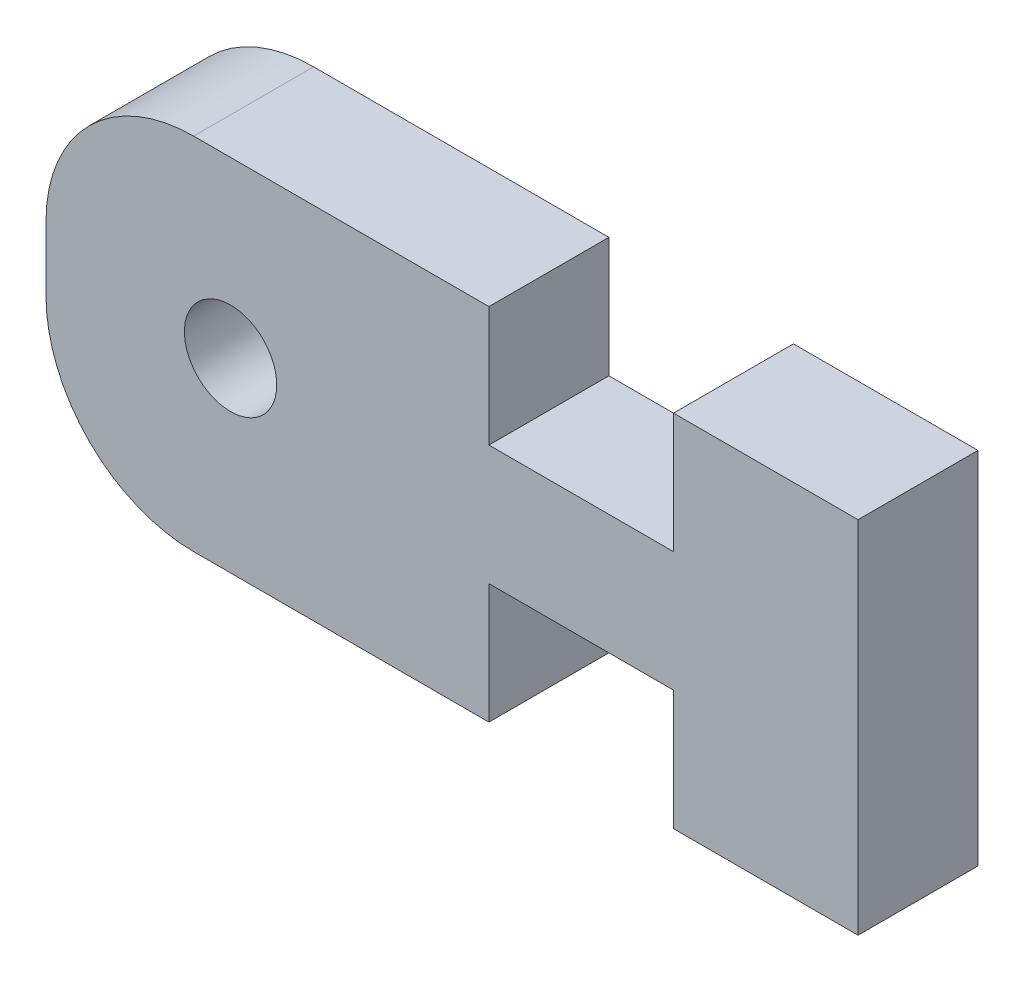
SolidWorks part; units mm, degrees
ref_plane "Front Plane" through (0, 0, 0) normal (0, 0, 1) x (1, 0, 0)
ref_plane "Top Plane" through (0, 0, 0) normal (0, 1, 0) x (1, 0, 0)
ref_plane "Right Plane" through (0, 0, 0) normal (1, 0, 0) x (0, 0, -1)
sketch "Sketch1" plane through (0, 0, 0) normal (0, 0, 1) x (1, 0, 0)
  line L1 (0, 0) -> (44, 0)
  line L2 (0, 0) -> (0, 19.5)
  line L3 (0, 19.5) -> (44, 19.5)
  line L4 (44, 0) -> (44, 19.5)
  dimension "D1" = 19.5
  dimension "D2" = 44
extrude "Boss-Extrude1" add sketch "Sketch1" along normal blind 6.5
sketch "Sketch2" plane through (0, 0, 6.5) normal (0, 0, 1) x (1, 0, 0)
  line L0 (44, 19.5) -> (0, 19.5) construction
  line L1 (34, 19.5) -> (24, 19.5)
  line L2 (34, 19.5) -> (34, 13)
  line L3 (34, 13) -> (24, 13)
  line L4 (24, 19.5) -> (24, 13)
  line L5 (0, 0) -> (44, 0) construction
  line L6 (34, 0) -> (24, 0)
  line L7 (34, 0) -> (34, 6.5)
  line L8 (34, 6.5) -> (24, 6.5)
  line L9 (24, 0) -> (24, 6.5)
  dimension "D1" = 6.5
  dimension "D2" = 10
  dimension "D3" = 10
  dimension "D4" = 10
  dimension "D5" = 6.5
extrude "Cut-Extrude1" cut sketch "Sketch2" against normal up to next
fillet "Fillet1" radius 8 2 edges at (0, 0, 3.25) (0, 19.5, 3.25)
sketch "Sketch3" plane through (0, 0, 6.5) normal (0, 0, 1) x (1, 0, 0)
  line L0 (0, 11.5) -> (0, 8) construction
  circle A0 centre (10, 10.0729) radius 2.5
  dimension "D1" = 5
  dimension "D2" = 10
extrude "Cut-Extrude2" cut sketch "Sketch3" against normal up to next
